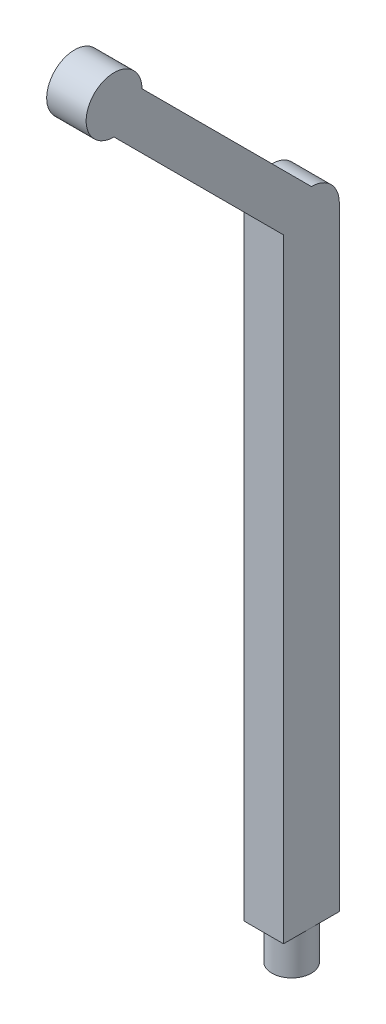
SolidWorks part; units mm, degrees
material "ABS"
ref_plane "前视基准面" through (0, 0, 0) normal (0, 0, 1) x (1, 0, 0)
ref_plane "上视基准面" through (0, 0, 0) normal (0, 1, 0) x (1, 0, 0)
ref_plane "右视基准面" through (0, 0, 0) normal (1, 0, 0) x (0, 0, -1)
other "质心 (COM)"
sketch "草图1" plane through (0, 0, 0) normal (1, 0, 0) x (0, 0, -1)
  line L0 (7.0711, 77.7817) -> (-42.9289, 127.7817)
  line L1 (-7.0711, 77.7817) -> (7.0711, 77.7817)
  line L2 (-7.0711, 77.7817) -> (-7.0711, -77.7817)
  line L3 (-7.0711, -77.7817) -> (7.0711, -77.7817)
  line L4 (7.0711, 77.7817) -> (7.0711, -77.7817)
  line L5 (-7.0711, 77.7817) -> (7.0711, -77.7817) construction
  line L6 (-7.0711, -77.7817) -> (7.0711, 77.7817) construction
  line L7 (-42.9289, 127.7817) -> (-57.0711, 127.7817)
  line L8 (-57.0711, 127.7817) -> (-7.0711, 77.7817)
  circle A2 centre (-50, 127.7817) radius 7.0711
  circle A3 centre (0, -77.7817) radius 7.0711
  circle A4 centre (0, 77.7817) radius 7.0711
  point P0 (0, 0)
extrude "凸台-拉伸2" add sketch "草图1" along normal blind 10 contours A4 L0 A2 L8 | L1 A4 | L0 A4 L1 | L0 A4 | A4 L2 A3 L4 | L3 A3
sketch "草图3" plane through (0, -77.7817, 0) normal (0, -1, 0) x (1, 0, 0)
  circle A0 centre (5, 0) radius 5
extrude "凸台-拉伸3" add sketch "草图3" along normal blind 10
sketch "草图4" plane through (10, 0, 0) normal (1, 0, 0) x (0, 0, -1)
  point P0 (0, 77.7817)
  point P1 (-50, 127.7817)
